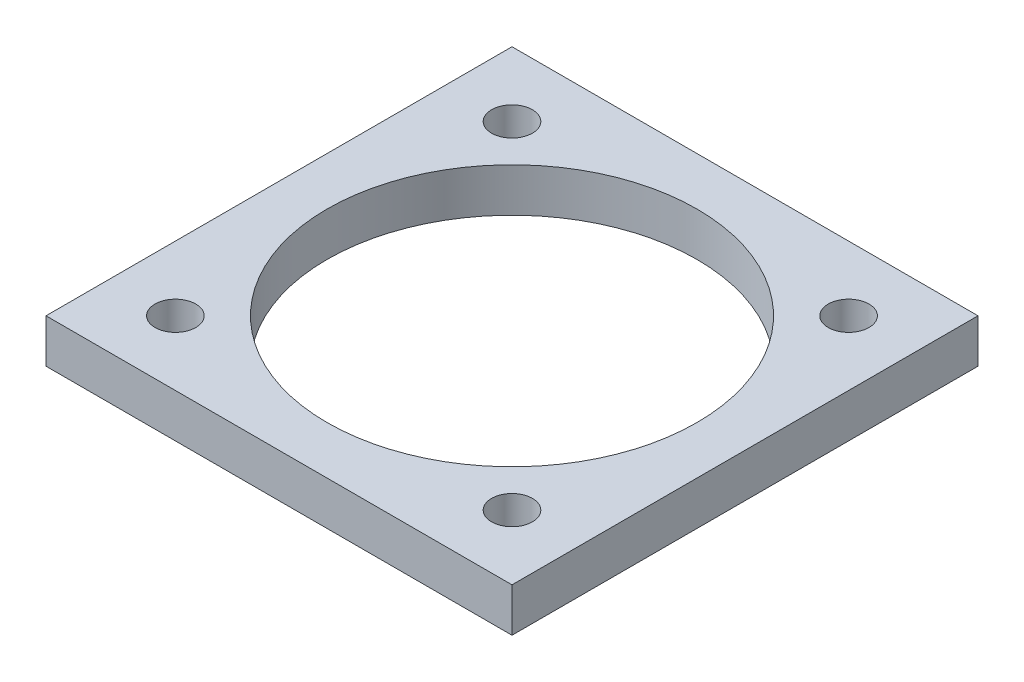
SolidWorks part; units mm, degrees
ref_plane "Front Plane" through (0, 0, 0) normal (0, 0, 1) x (1, 0, 0)
ref_plane "Top Plane" through (0, 0, 0) normal (0, 1, 0) x (1, 0, 0)
ref_plane "Right Plane" through (0, 0, 0) normal (1, 0, 0) x (0, 0, -1)
sketch "Sketch1" plane through (0, 0, 0) normal (0, 1, 0) x (1, 0, 0)
  line L1 (16, -16) -> (-16, -16)
  line L2 (16, -16) -> (16, 16)
  line L3 (16, 16) -> (-16, 16)
  line L4 (-16, -16) -> (-16, 16)
  line L5 (16, -16) -> (-16, 16) construction
  line L6 (16, 16) -> (-16, -16) construction
  line L7 (11.557, -11.557) -> (-11.557, -11.557) construction
  line L8 (11.557, -11.557) -> (11.557, 11.557) construction
  line L9 (11.557, 11.557) -> (-11.557, 11.557) construction
  line L10 (-11.557, -11.557) -> (-11.557, 11.557) construction
  line L11 (11.557, -11.557) -> (-11.557, 11.557) construction
  line L12 (11.557, 11.557) -> (-11.557, -11.557) construction
  circle A0 centre (-11.557, -11.557) radius 1.4
  circle A1 centre (11.557, -11.557) radius 1.4
  circle A2 centre (11.557, 11.557) radius 1.4
  circle A3 centre (-11.557, 11.557) radius 1.4
  circle A4 centre (0, 0) radius 12.7
  point P0 (0, 0)
  point P6 (0, 0)
  dimension "D3" = 2.8
  dimension "D4" = 25.4
  dimension "D1" = 32
  dimension "D2" = 23.114
extrude "Boss-Extrude1" add sketch "Sketch1" along normal blind 3
